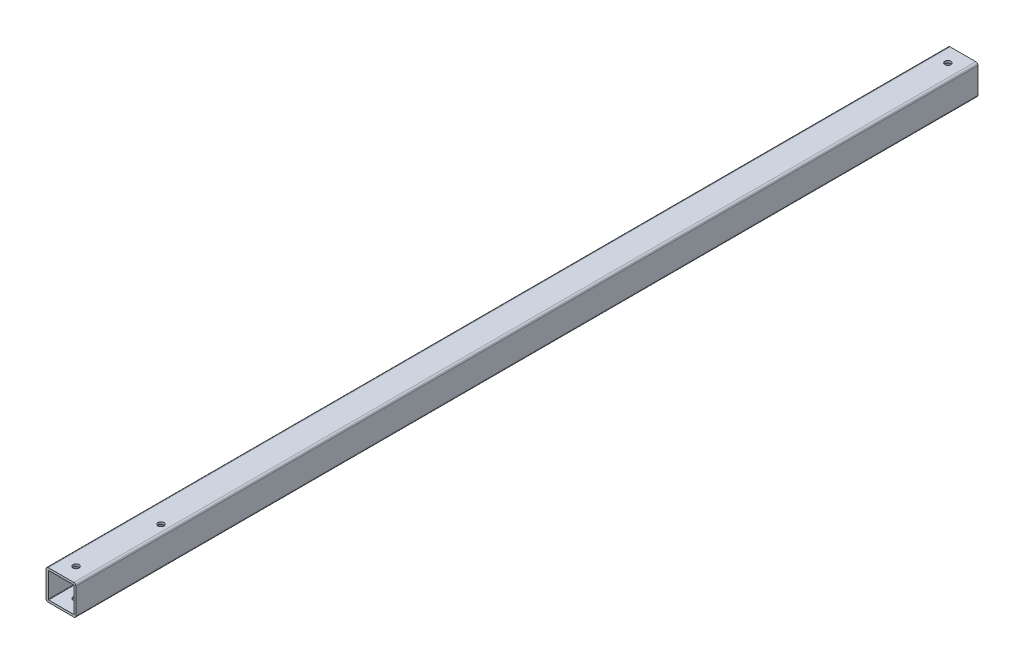
SolidWorks part; units mm, degrees
ref_plane "Front Plane" through (0, 0, 0) normal (0, 0, 1) x (1, 0, 0)
ref_plane "Top Plane" through (0, 0, 0) normal (0, 1, 0) x (1, 0, 0)
ref_plane "Right Plane" through (0, 0, 0) normal (1, 0, 0) x (0, 0, -1)
sketch "Sketch1" plane through (0, 0, 0) normal (0, 0, 1) x (1, 0, 0)
  line L1 (-20, 20) -> (20, 20)
  line L2 (-20, 20) -> (-20, -20)
  line L3 (-20, -20) -> (20, -20)
  line L4 (20, 20) -> (20, -20)
  line L5 (-20, 20) -> (20, -20) construction
  line L6 (-20, -20) -> (20, 20) construction
  point P0 (0, 0)
  dimension "D1" = 40
  dimension "D2" = 40
extrude "Extrude-Thin1" add sketch "Sketch1" along normal blind 1200 thin
fillet "Fillet1" radius 0.5 4 edges at (-17, -17, 600) (-17, 17, 600) (17, 17, 600) (17, -17, 600)
fillet "Fillet2" radius 3 4 edges at (20, -20, 600) (-20, -20, 600) (20, 20, 600) (-20, 20, 600)
hole_wizard "Ø8.0 (8) Diameter Hole1" positions "Sketch4" profile "Sketch3" hole size "Ø8.0" standard "ANSI Metric" end condition through all
sketch "Sketch4" plane through (0, 20, 0) normal (0, 1, 0) x (1, 0, 0)
  line L0 (0, 0) -> (0, -1200) construction
  line L1 (17, -1200) -> (-17, -1200) construction
  point P8 (0, -20)
  point P10 (0, -1180)
  dimension "D1" = 20
  dimension "D2" = 20
sketch "Sketch3" plane through (0, 20, 20) normal (1, 0, 0) x (0, 0, 1)
  line L0 (0, 0) -> (0, 40)
  line L1 (0, 40) -> (4, 40)
  line L2 (4, 40) -> (4, 0)
  line L5 (4, 0) -> (0, 0)
  line L11 (0, -6.35) -> (0, 107.95) construction
  dimension "Thru Hole Dia." = 8
  dimension "Thru Hole Depth" = 40
sketch "Sketch5" plane through (0, 20, 0) normal (0, 1, 0) x (1, 0, 0)
  line L0 (20, 0) -> (20, -1200) construction
  line L1 (-60, -1200) -> (20, -1200) construction
  circle A0 centre (8, -1075) radius 4
  dimension "D2" = 125
  dimension "D3" = 8
  dimension "D1" = 12
extrude "Cut-Extrude1" cut sketch "Sketch5" against normal through all
equation "\"a\"= \"Beam Profile@Plasma Beta.Assembly\""
equation "\"b\"= 3"
equation "\"L\"= \"Lenght@Plasma Beta.Assembly\""
equation "\"D2@Sketch1\"=\"a\""
equation "\"D1@Sketch1\"=\"a\""
equation "\"D1@Extrude-Thin1\"=\"L\""
equation "\"D5@Extrude-Thin1\"=\"b\""
equation "\"D1@Fillet2\"=\"b\""
